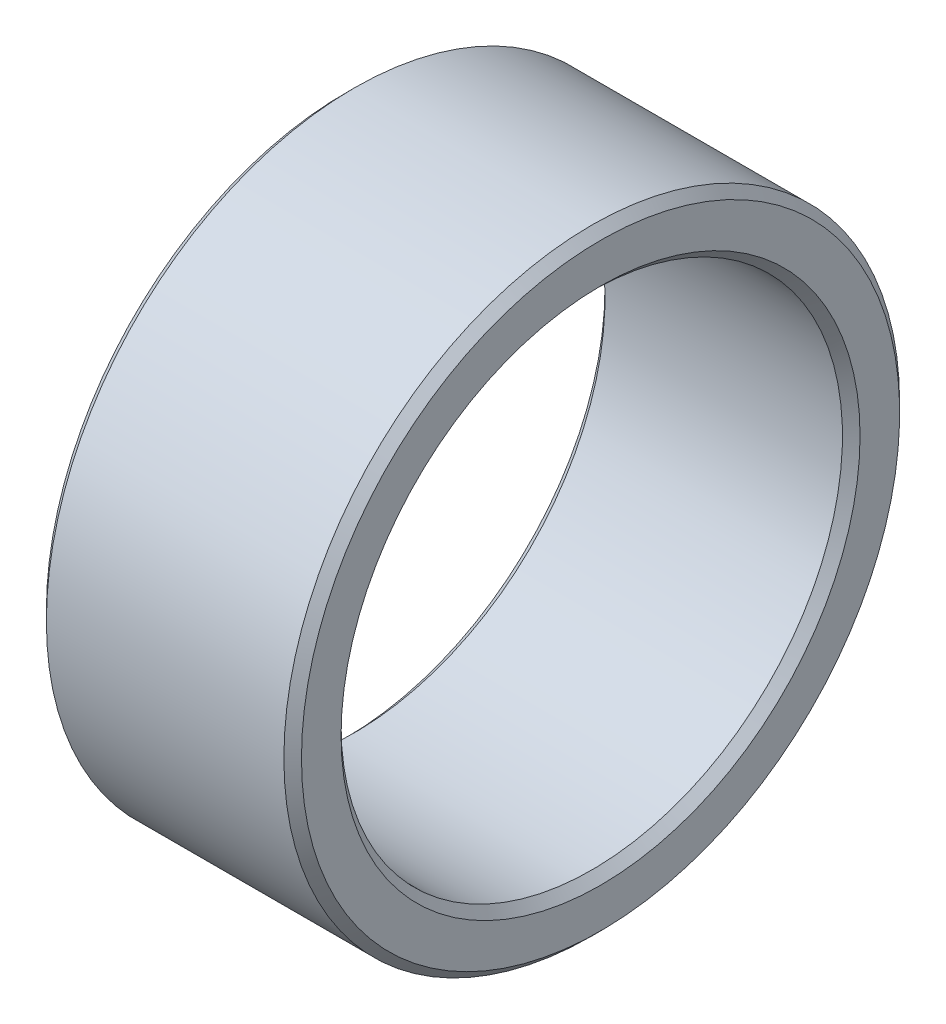
SolidWorks part; units mm, degrees
material "1.7131 (16MnCr5)"
ref_plane "Vorne" through (0, 0, 0) normal (0, 0, 1) x (1, 0, 0)
ref_plane "Oben" through (0, 0, 0) normal (0, 1, 0) x (1, 0, 0)
ref_plane "Rechts" through (0, 0, 0) normal (1, 0, 0) x (0, 0, -1)
sketch "Skizze1" plane through (0, 0, 0) normal (0, 0, 1) x (1, 0, 0)
  line L0 (0, 0) -> (22.2384, 0) construction
  line L1 (8.4, 10.5) -> (8.7, 10.2)
  line L2 (0.3, 10.5) -> (8.4, 10.5)
  line L3 (0, 10.2) -> (0, 8.85)
  line L4 (0.3, 8.55) -> (8.4, 8.55)
  line L5 (8.7, 10.2) -> (8.7, 8.85)
  line L6 (8.4, 8.55) -> (8.7, 8.85)
  line L7 (0, 8.85) -> (0.3, 8.55)
  line L8 (0, 10.2) -> (0.3, 10.5)
  point P3 (0, 10.5)
  point P4 (8.7, 8.55)
  point P5 (0, 8.55)
  point P6 (8.7, 10.5)
  dimension "D1" = 17.1
  dimension "D2" = 21
  dimension "D3" = 8.7
revolve "Rotation1" add sketch "Skizze1" angle 360 about L0
